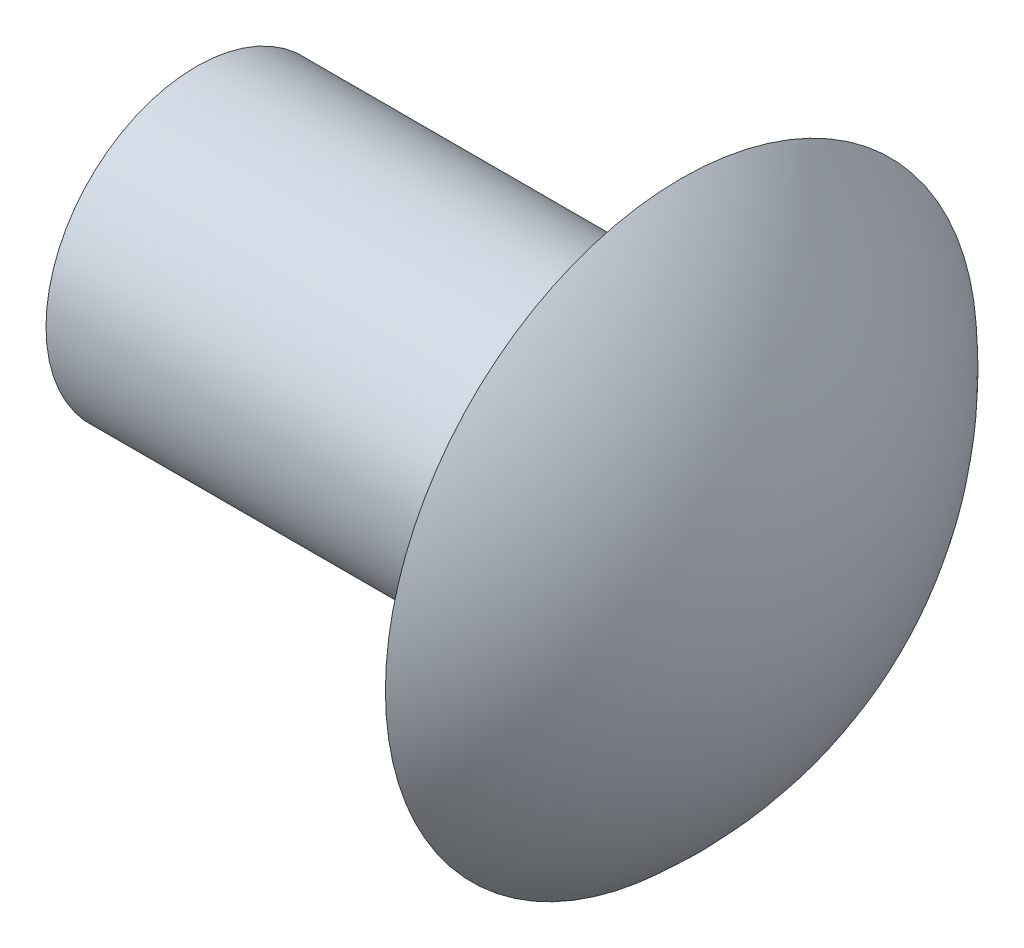
SolidWorks part; units mm, degrees
ref_plane "Plan de face" through (0, 0, 0) normal (0, 0, 1) x (1, 0, 0)
ref_plane "Plan de dessus" through (0, 0, 0) normal (0, 1, 0) x (1, 0, 0)
ref_plane "Plan de droite" through (0, 0, 0) normal (1, 0, 0) x (0, 0, -1)
sketch "Esquisse1" plane through (0, 0, 0) normal (0, 0, 1) x (1, 0, 0)
  line L0 (0, 0) -> (-5, 0)
  line L1 (-5, 0) -> (-5, -1.55)
  line L2 (-5, -1.55) -> (0, -1.55)
  line L3 (0, -1.55) -> (0, -3.05)
  line L4 (0, 0) -> (1.3734, 0)
  arc A0 (0, -3.05) -> (1.3734, 0) centre (-2.7, 0) ccw
  point P8 (-5.0049, 0)
  point P9 (-3.5739, 1.5952)
  point P10 (0, 0)
  point P11 (-2.8172, 0)
  dimension "D1" = 1.55
  dimension "D2" = 1.5
  dimension "D3" = 2.7
  dimension "D4" = 5
revolve "Révolution1" add sketch "Esquisse1" angle 360 about L0
